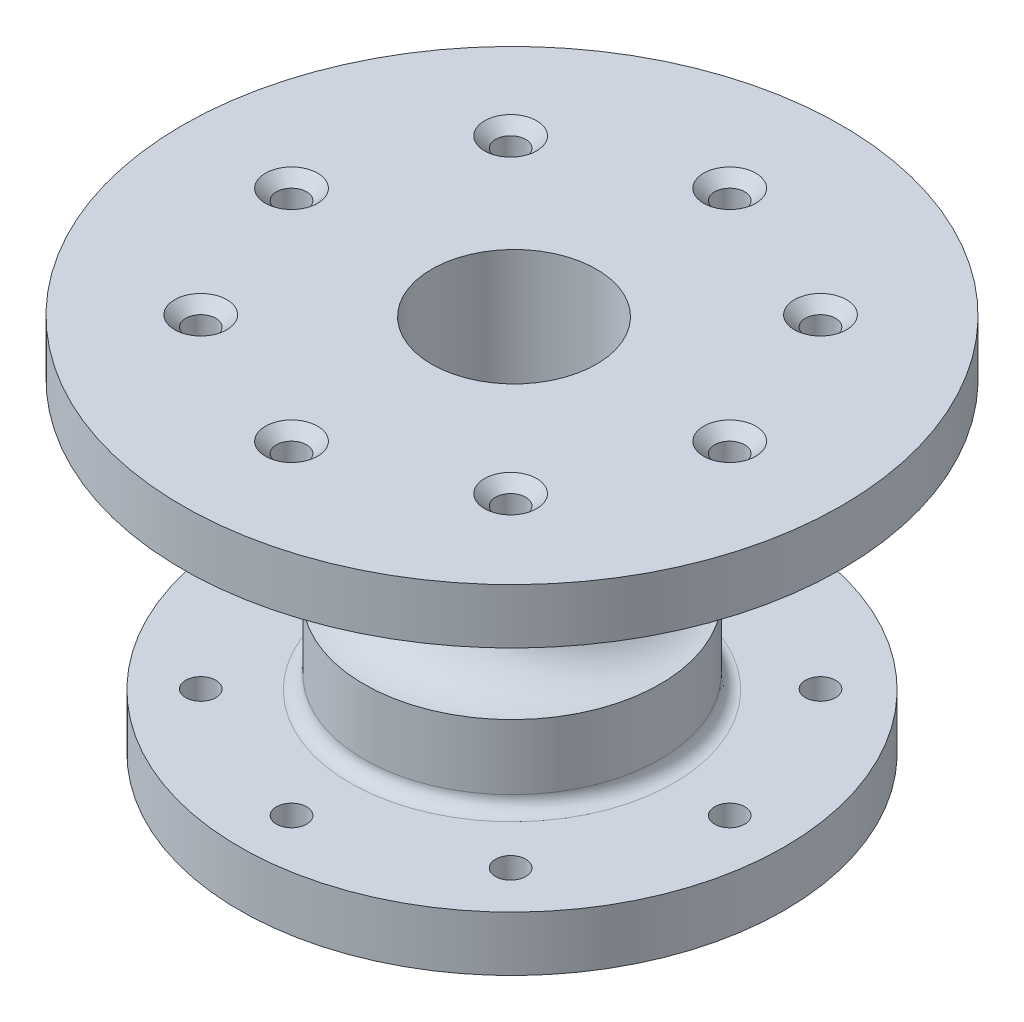
SolidWorks part; units mm, degrees
ref_plane "Front Plane" through (0, 0, 0) normal (0, 0, 1) x (1, 0, 0)
ref_plane "Top Plane" through (0, 0, 0) normal (0, 1, 0) x (1, 0, 0)
ref_plane "Right Plane" through (0, 0, 0) normal (1, 0, 0) x (0, 0, -1)
sketch "Sketch1" plane through (0, 0, 0) normal (0, 0, 1) x (1, 0, 0)
  line L1 (-0.743, 69.0036) -> (119.257, 69.0036)
  line L2 (119.257, 69.0036) -> (119.257, 49.0036)
  line L3 (119.257, 49.0036) -> (58.1459, 49.0036)
  line L4 (53.1459, 44.0036) -> (53.1459, 19.6785)
  line L5 (58.1459, -49.0036) -> (98.4237, -49.0036)
  line L6 (98.4237, -49.0036) -> (98.4237, -69.0036)
  line L7 (98.4237, -69.0036) -> (-0.743, -69.0036)
  line L9 (-138.0556, 0) -> (-12.886, 0) construction
  line L10 (-0.743, 69.0036) -> (-0.743, 7.7042)
  line L11 (73.8889, 0) -> (148.3333, 0) construction
  line L12 (53.1459, -20.3215) -> (53.1459, -44.0036)
  line L13 (12, 0) -> (25.8889, 0) construction
  line L15 (-0.743, -7.7042) -> (-0.743, -69.0036)
  arc A0 (53.1459, -44.0036) -> (58.1459, -49.0036) centre (58.1459, -44.0036) ccw
  arc A1 (58.1459, 49.0036) -> (53.1459, 44.0036) centre (58.1459, 44.0036) ccw
  arc A2 (53.1459, 19.6785) -> (53.1459, -20.3215) centre (53.1459, -0.3215) ccw
  arc A3 (-0.743, -7.7042) -> (-0.743, 7.7042) centre (0, 0) ccw
  dimension "D5" = 5
  dimension "D1" = 120
  dimension "D2" = 99.1667
  dimension "D3" = 20
  dimension "D4" = 20
revolve "Revolve1" add sketch "Sketch1" angle 360 about L10
hole_wizard "CSK for M10 Cross Countersunk Head Screw1" positions "Sketch2" profile "Sketch3" countersink size "M10" standard "AS" end condition through all
sketch "Sketch2" plane through (0, 69.0036, 0) normal (0, 1, 0) x (1, 0, 0)
  point P0 (78.5341, 0)
sketch "Sketch3" plane through (78.5341, 69.0036, 0) normal (1, 0, 0) x (0, 0, 1)
  line L0 (0, 0) -> (0, 138.0071)
  line L1 (0, 138.0071) -> (5.5, 138.0071)
  line L2 (5.5, 138.0071) -> (5.5, 3.8628)
  line L3 (5.5, 3.8628) -> (9.5, 0)
  line L5 (9.5, 0) -> (0, 0)
  line L6 (-5.5, 3.8628) -> (-9.5, 0) construction
  line L11 (0, -6.35) -> (0, 107.95) construction
  dimension "Thru Hole Dia." = 11
  dimension "Thru Hole Depth" = 138.0071
  dimension "Near C'Sink Dia." = 19
  dimension "Near C'Sink Angle" = 92
pattern_circular "CirPattern1" count 8 over 360 about axis through (-1.243, 0, 0) along (0, 1, 0) of "CSK for M10 Cross Countersunk Head Screw1"
sketch "Sketch4" plane through (0, 69.0036, 0) normal (0, 1, 0) x (1, 0, 0)
  circle A0 centre (0, 0) radius 30
extrude "Cut-Extrude1" cut sketch "Sketch4" against normal blind 88
